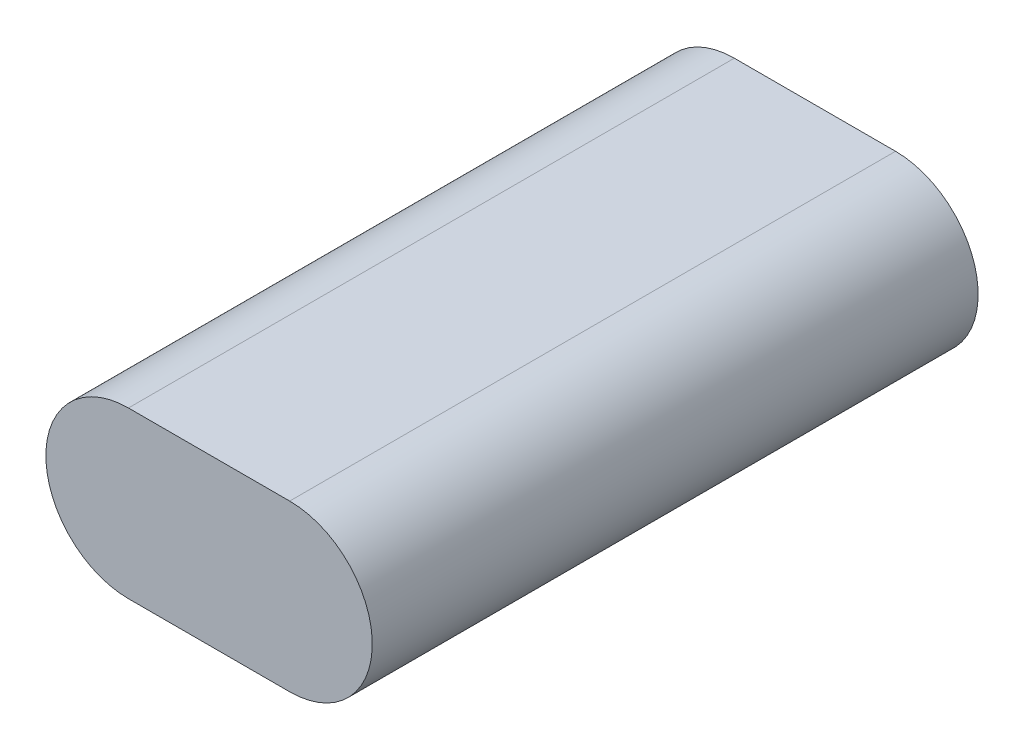
SolidWorks part; units mm, degrees
ref_plane "Front Plane" through (0, 0, 0) normal (0, 0, 1) x (1, 0, 0)
ref_plane "Top Plane" through (0, 0, 0) normal (0, 1, 0) x (1, 0, 0)
ref_plane "Right Plane" through (0, 0, 0) normal (1, 0, 0) x (0, 0, -1)
sketch "Sketch1" plane through (0, 0, 0) normal (0, 0, 1) x (1, 0, 0)
  line L0 (0, 0) -> (0, 16.7) construction
  line L1 (0, 0) -> (33, 0) construction
  line L2 (-16.3, 16.7) -> (16.3, 16.7)
  line L3 (16.3, -16.7) -> (-16.3, -16.7)
  circle A0 centre (33, 0) radius 16.7 construction
  circle A1 centre (16.3, 0) radius 16.7 construction
  arc A2 (16.3, 16.7) -> (16.3, -16.7) centre (16.3, 0) cw
  arc A3 (-16.3, 16.7) -> (-16.3, -16.7) centre (-16.3, 0) ccw
  point P13 (0, -16.7)
extrude "Extrude1" add sketch "Sketch1" against normal blind 122.5
sketch "Sketch2" plane through (0, 16.7, 0) normal (0, 1, 0) x (1, 0, 0)
  line L0 (0, 0) -> (0, 122.5) construction
  line L1 (16.3, 0) -> (-16.3, 0) construction
  line L2 (16.3, 122.5) -> (-16.3, 122.5) construction
  circle A0 centre (0, 61.25) radius 7.1736 construction
